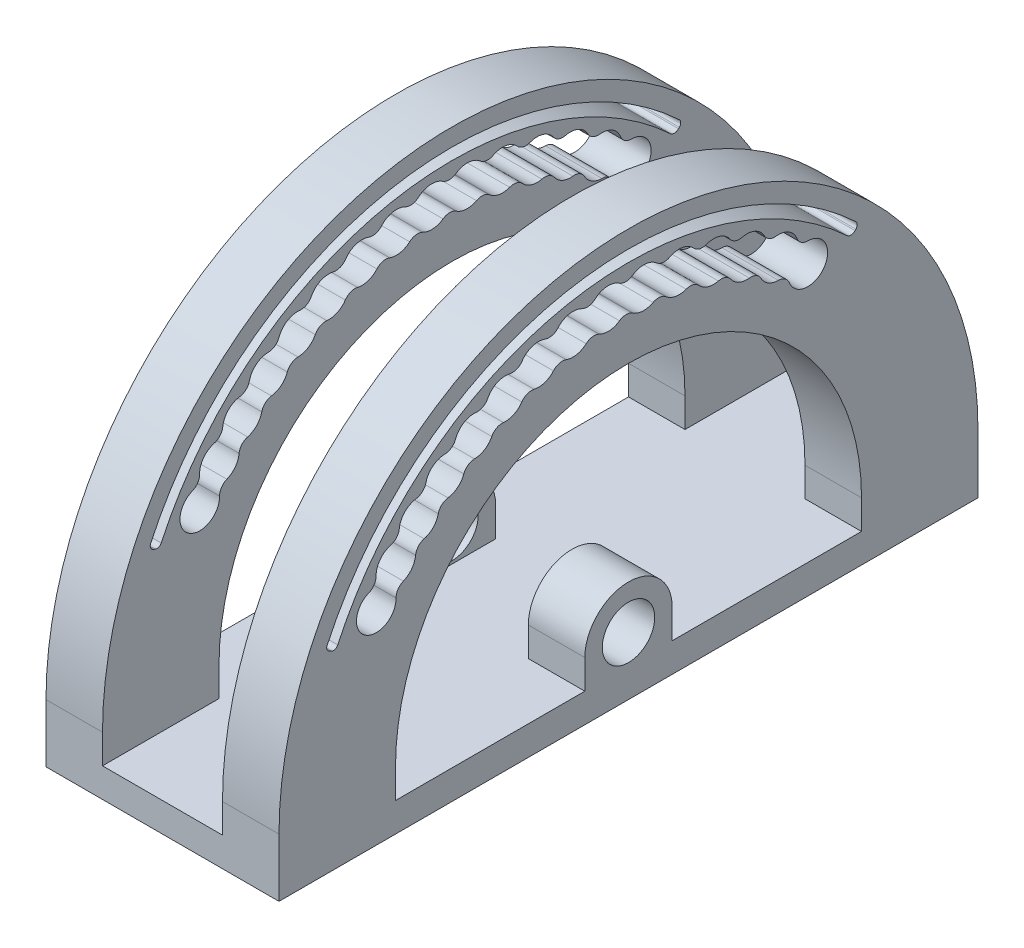
SolidWorks part; units mm, degrees
ref_plane "前视基准面" through (0, 0, 0) normal (0, 0, 1) x (1, 0, 0)
ref_plane "上视基准面" through (0, 0, 0) normal (0, 1, 0) x (1, 0, 0)
ref_plane "右视基准面" through (0, 0, 0) normal (1, 0, 0) x (0, 0, -1)
other "Configuration Table"
sketch "草图1" plane through (0, 0, 0) normal (0, 1, 0) x (1, 0, 0)
  line L1 (-20, -60) -> (20, -60)
  line L2 (-20, -60) -> (-20, 60)
  line L3 (-20, 60) -> (20, 60)
  line L4 (20, -60) -> (20, 60)
  line L5 (-20, -60) -> (20, 60) construction
  line L6 (-20, 60) -> (20, -60) construction
  point P0 (0, 0)
  dimension "D1" = 120
  dimension "D2" = 40
extrude "凸台-拉伸1" add sketch "草图1" along normal blind 5
sketch "草图2" plane through (20, 0, 0) normal (1, 0, 0) x (0, 0, -1)
  line L0 (-60, 5) -> (60, 5) construction
  line L1 (-7.5, 5) -> (7.5, 5)
  line L2 (-7.5, 5) -> (-7.5, 10)
  line L4 (7.5, 5) -> (7.5, 10)
  arc A0 (-7.5, 10) -> (7.5, 10) centre (0, 10) cw
  circle A1 centre (0, 10) radius 4.5
  dimension "D4" = 7.5
  dimension "D5" = 9
  dimension "D1" = 5
  dimension "D2" = 7.5
  dimension "D3" = 7.5
  dimension "D6" = 5
extrude "凸台-拉伸5" add sketch "草图2" against normal blind 9.7
mirror "镜向1" about plane through (0, 0, 0) normal (1, 0, 0) of "凸台-拉伸5"
sketch "草图3" plane through (20, 0, 0) normal (1, 0, 0) x (0, 0, -1)
  line L0 (-60, 10) -> (-60, 5)
  line L1 (-60, 5) -> (-40, 5)
  line L2 (-60, 5) -> (-7.5, 5) construction
  line L4 (-40, 5) -> (-40, 10)
  line L6 (40, 10) -> (40, 5)
  line L7 (7.5, 5) -> (60, 5) construction
  line L8 (40, 5) -> (60, 5)
  line L9 (60, 5) -> (60, 10)
  arc A0 (60, 10) -> (-60, 10) centre (0, 10) ccw
  arc A1 (40, 10) -> (-40, 10) centre (0, 10) ccw
  dimension "D1" = 40
  dimension "D2" = 20
  dimension "D3" = 20
extrude "凸台-拉伸6" add sketch "草图3" against normal blind 9.7 contours A1 L4 L1 L0 A0 L9 L8 L6
sketch "草图4" plane through (20, 0, 0) normal (1, 0, 0) x (0, 0, -1)
  line L0 (0, 10) -> (-50, 10) construction
  line L1 (0, 10) -> (30.7831, 49.4005) construction
  line L2 (0, 10) -> (-43.3013, 35) construction
  line L3 (0, 10) -> (-39.9318, 40.0908) construction
  line L4 (0, 10) -> (-35.967, 44.7329) construction
  line L5 (0, 10) -> (-31.466, 48.8573) construction
  line L6 (0, 10) -> (-26.496, 52.4024) construction
  line L7 (0, 10) -> (-21.1309, 55.3154) construction
  line L8 (0, 10) -> (-15.4508, 57.5528) construction
  line L9 (0, 10) -> (-9.5404, 59.0814) construction
  line L10 (0, 10) -> (-3.4878, 59.8782) construction
  line L11 (0, 10) -> (2.6168, 59.9315) construction
  line L12 (0, 10) -> (8.6824, 59.2404) construction
  line L13 (0, 10) -> (14.6186, 57.8152) construction
  line L14 (0, 10) -> (20.3368, 55.6773) construction
  line L15 (0, 10) -> (25.7519, 52.8584) construction
  circle A0 centre (0, 10) radius 50 construction
  arc A1 (-44.5793, 38.1507) -> (-39.9017, 35.0546) centre (-43.3013, 35) ccw
  arc A2 (-38.6537, 36.9401) -> (-36.5509, 39.7307) centre (-39.9318, 40.0908) ccw
  arc A3 (-35.0825, 41.45) -> (-32.6552, 43.9635) centre (-35.967, 44.7329) ccw
  arc A4 (-30.9882, 45.491) -> (-28.2727, 47.69) centre (-31.466, 48.8573) ccw
  arc A5 (-26.4319, 49.003) -> (-23.4687, 50.8546) centre (-26.496, 52.4024) ccw
  arc A6 (-21.4816, 51.9335) -> (-18.3148, 53.4102) centre (-21.1309, 55.3154) ccw
  arc A8 (-10.6989, 55.8848) -> (-7.2689, 56.5515) centre (-9.5404, 59.0814) ccw
  arc A9 (-5.0272, 56.8466) -> (-1.5415, 57.0904) centre (-3.4878, 59.8782) ccw
  arc A10 (0.7194, 57.1101) -> (4.2088, 56.9272) centre (2.6168, 59.9315) ccw
  arc A12 (6.4554, 56.6713) -> (9.8965, 56.0645) centre (8.6824, 59.2404) ccw
  arc A13 (12.095, 55.5367) -> (15.4365, 54.5151) centre (14.6186, 57.8152) ccw
  arc A14 (17.5544, 53.7233) -> (20.7465, 52.302) centre (20.3368, 55.6773) ccw
  arc A15 (22.7521, 51.258) -> (25.7472, 49.4584) centre (25.7519, 52.8584) ccw
  arc A16 (27.6106, 48.1777) -> (30.7878, 52.8005) centre (30.7831, 49.4005) ccw
  arc A17 (-40.8163, 43.3737) -> (-43.3313, 40.0361) centre (-39.9318, 40.0908) ccw
  arc A18 (-36.4448, 48.0992) -> (-39.3479, 45.093) centre (-35.967, 44.7329) ccw
  arc A19 (-31.5301, 52.2567) -> (-34.7778, 49.6267) centre (-31.466, 48.8573) ccw
  arc A20 (-26.1453, 55.7843) -> (-29.6893, 53.5697) centre (-26.496, 52.4024) ccw
  arc A21 (-16.2111, 54.2389) -> (-12.8879, 55.3187) centre (-15.4508, 57.5528) ccw
  arc A22 (-20.3707, 58.6293) -> (-24.1582, 56.8632) centre (-21.1309, 55.3154) ccw
  arc A23 (-14.2924, 60.7494) -> (-18.2669, 59.458) centre (-15.4508, 57.5528) ccw
  arc A24 (-8.0011, 62.1129) -> (-12.1034, 61.3155) centre (-9.5404, 59.0814) ccw
  arc A25 (-1.5905, 62.6996) -> (-5.7594, 62.408) centre (-3.4878, 59.8782) ccw
  arc A26 (4.8438, 62.5006) -> (0.6705, 62.7193) centre (2.6168, 59.9315) ccw
  arc A27 (11.2059, 61.5189) -> (7.0904, 62.2446) centre (8.6824, 59.2404) ccw
  arc A28 (17.401, 59.7693) -> (13.4045, 60.9911) centre (14.6186, 57.8152) ccw
  arc A29 (23.3366, 57.2776) -> (19.5189, 58.9774) centre (20.3368, 55.6773) ccw
  arc A30 (28.9244, 54.0812) -> (25.3422, 56.2336) centre (25.7519, 52.8584) ccw
  arc A31 (-40.8163, 43.3737) -> (-39.3479, 45.093) centre (-41.3366, 45.3048) ccw
  arc A32 (-39.9017, 35.0546) -> (-38.6537, 36.9401) centre (-37.902, 35.0868) cw
  arc A33 (-44.5793, 38.1507) -> (-43.3313, 40.0361) centre (-45.3311, 40.004) ccw
  arc A34 (-36.5509, 39.7307) -> (-35.0825, 41.45) centre (-34.5621, 39.5189) cw
  arc A35 (-32.6552, 43.9635) -> (-30.9882, 45.491) centre (-30.7071, 43.5109) cw
  arc A36 (-34.7778, 49.6267) -> (-36.4448, 48.0992) centre (-36.7259, 50.0793) cw
  arc A37 (-28.2727, 47.69) -> (-26.4319, 49.003) centre (-26.3942, 47.0034) cw
  arc A38 (-29.6893, 53.5697) -> (-31.5301, 52.2567) centre (-31.5677, 54.2563) cw
  arc A39 (-26.1453, 55.7843) -> (-24.1582, 56.8632) centre (-25.9389, 57.7736) ccw
  arc A40 (-21.4816, 51.9335) -> (-23.4687, 50.8546) centre (-21.6879, 49.9442) ccw
  arc A41 (-20.3707, 58.6293) -> (-18.2669, 59.458) centre (-19.9235, 60.5787) ccw
  arc A42 (-16.2111, 54.2389) -> (-18.3148, 53.4102) centre (-16.6583, 52.2896) ccw
  arc A43 (-10.6989, 55.8848) -> (-12.8879, 55.3187) centre (-11.3803, 54.0045) ccw
  arc A44 (-14.2924, 60.7494) -> (-12.1034, 61.3155) centre (-13.611, 62.6297) ccw
  arc A45 (-7.2689, 56.5515) -> (-5.0272, 56.8466) centre (-5.9327, 55.0634) cw
  arc A46 (-8.0011, 62.1129) -> (-5.7594, 62.408) centre (-7.0956, 63.8962) ccw
  arc A47 (-1.5415, 57.0904) -> (0.7194, 57.1101) centre (-0.3966, 55.4505) cw
  arc A48 (0.6705, 62.7193) -> (-1.5905, 62.6996) centre (-0.4744, 64.3592) cw
  arc A49 (6.4554, 56.6713) -> (4.2088, 56.9272) centre (5.1453, 55.1601) ccw
  arc A50 (4.8438, 62.5006) -> (7.0904, 62.2446) centre (6.1539, 64.0118) ccw
  arc A51 (12.095, 55.5367) -> (9.8965, 56.0645) centre (10.6106, 54.1964) ccw
  arc A52 (11.2059, 61.5189) -> (13.4045, 60.9911) centre (12.6904, 62.8592) ccw
  arc A53 (17.401, 59.7693) -> (19.5189, 58.9774) centre (19.0377, 60.9187) ccw
  arc A54 (15.4365, 54.5151) -> (17.5544, 53.7233) centre (15.9177, 52.5738) cw
  arc A55 (20.7465, 52.302) -> (22.7521, 51.258) centre (20.9875, 50.3166) cw
  arc A56 (23.3366, 57.2776) -> (25.3422, 56.2336) centre (25.1012, 58.219) ccw
  arc A57 (25.7472, 49.4584) -> (27.6106, 48.1777) centre (25.7444, 47.4584) cw
  arc A58 (28.9244, 54.0812) -> (30.7878, 52.8005) centre (30.7906, 54.8005) ccw
  dimension "D1" = 100
  dimension "D17" = 6.8
  dimension "D18" = 6.8
  dimension "D19" = 6.8
  dimension "D20" = 6.8
  dimension "D21" = 6.8
  dimension "D22" = 6.8
  dimension "D23" = 6.8
  dimension "D24" = 6.8
  dimension "D25" = 6.8
  dimension "D26" = 6.8
  dimension "D27" = 6.8
  dimension "D28" = 6.8
  dimension "D29" = 6.8
  dimension "D30" = 6.8
  dimension "D31" = 6.8
  dimension "D32" = 2
  dimension "D33" = 2
  dimension "D34" = 2
  dimension "D35" = 2
  dimension "D36" = 2
  dimension "D37" = 2
  dimension "D38" = 2
  dimension "D39" = 2
  dimension "D40" = 2
  dimension "D41" = 2
  dimension "D42" = 2
  dimension "D43" = 2
  dimension "D44" = 2
  dimension "D45" = 2
  dimension "D46" = 2
  dimension "D2" = 30
  dimension "D3" = 98
  dimension "D4" = 7
  dimension "D5" = 7
  dimension "D6" = 7
  dimension "D7" = 7
  dimension "D8" = 7
  dimension "D9" = 7
  dimension "D10" = 7
  dimension "D11" = 7
  dimension "D12" = 7
  dimension "D13" = 7
  dimension "D14" = 7
  dimension "D15" = 7
  dimension "D16" = 7
extrude "切除-拉伸1" cut sketch "草图4" against normal blind 9.7
sketch "草图5" plane through (20, 0, 0) normal (1, 0, 0) x (0, 0, -1)
  line L0 (-50.245, 32.3705) -> (0, 10) construction
  line L1 (0, 10) -> (38.2062, 49.5637) construction
  line L2 (-40, 5) -> (-7.5, 5) construction
  line L3 (7.5, 5) -> (40, 5) construction
  line L4 (-50.9706, 32.6936) -> (-51.3361, 32.8563)
  line L5 (38.8947, 50.2766) -> (39.0358, 50.4228)
  arc A0 (-49.9191, 33.0886) -> (37.4936, 50.2396) centre (0, 10) cw
  arc A1 (-51.7368, 33.9229) -> (39.0079, 51.5619) centre (0, 10) cw
  arc A2 (39.0079, 51.5619) -> (39.0358, 50.4228) centre (38.4604, 50.9785) cw
  arc A3 (-51.7368, 33.9229) -> (-51.3361, 32.8563) centre (-51.0107, 33.5871) ccw
  arc A4 (-49.9191, 33.0886) -> (-50.9706, 32.6936) centre (-50.6452, 33.4244) cw
  arc A5 (37.4936, 50.2396) -> (38.8947, 50.2766) centre (38.1753, 50.9713) ccw
  point P10 (-52.5011, 32.9621)
  point P11 (40.9604, 50.5387)
  dimension "D1" = 55
  dimension "D4" = 57
  dimension "D5" = 0.8
  dimension "D6" = 1
  dimension "D2" = 24
  dimension "D3" = 46
extrude "切除-拉伸2" cut sketch "草图5" against normal blind 9.7
mirror "镜向2" about plane through (0, 0, 0) normal (1, 0, 0) of "凸台-拉伸6", "切除-拉伸2", "切除-拉伸1"
